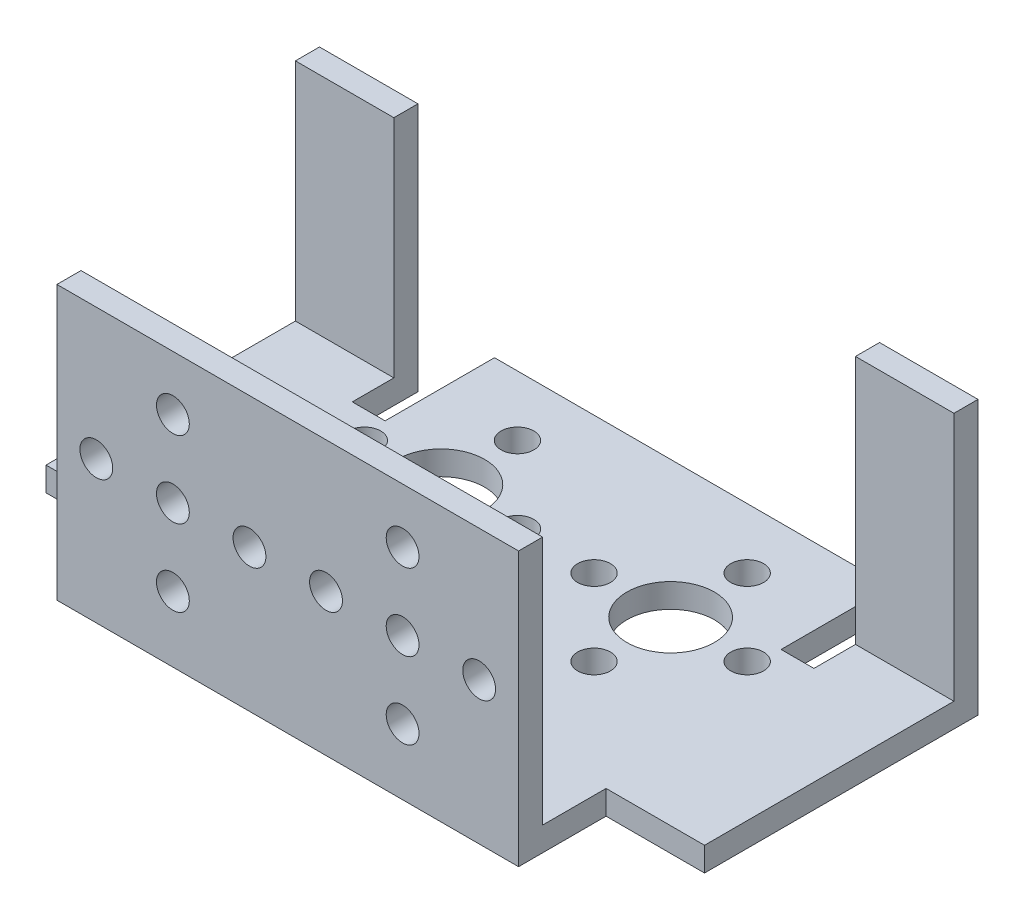
SolidWorks part; units mm, degrees
ref_plane "Front Plane" through (0, 0, 0) normal (0, 0, 1) x (1, 0, 0)
ref_plane "Top Plane" through (0, 0, 0) normal (0, 1, 0) x (1, 0, 0)
ref_plane "Right Plane" through (0, 0, 0) normal (1, 0, 0) x (0, 0, -1)
sketch "Sketch1" plane through (0, 0, 0) normal (0, 1, 0) x (1, 0, 0)
  line L0 (0, 0) -> (0, 37) construction
  line L1 (21.1, 0) -> (-21.1, 0)
  line L2 (-21.1, 0) -> (-21.1, 8)
  line L3 (-21.1, 8) -> (-30.1, 8)
  line L4 (-30.1, 8) -> (-30.1, 33)
  line L5 (-30.1, 33) -> (-21.1, 33)
  line L6 (-21.1, 33) -> (-21.1, 27)
  line L7 (-21.1, 27) -> (-18.1, 27)
  line L8 (-18.1, 27) -> (-18.1, 37)
  line L9 (-18.1, 37) -> (18.1, 37)
  line L10 (18.1, 27) -> (18.1, 37)
  line L11 (21.1, 27) -> (18.1, 27)
  line L12 (21.1, 33) -> (21.1, 27)
  line L13 (30.1, 33) -> (21.1, 33)
  line L14 (30.1, 8) -> (30.1, 33)
  line L15 (21.1, 8) -> (30.1, 8)
  line L16 (21.1, 0) -> (21.1, 8)
  dimension "D1" = 9
  dimension "D2" = 21.1
  dimension "D3" = 37
  dimension "D4" = 8
  dimension "D5" = 25
  dimension "D6" = 6
  dimension "D7" = 3
extrude "Boss-Extrude1" add sketch "Sketch1" along normal blind 2.2
sketch "Sketch2" plane through (0, 2.2, 0) normal (0, 1, 0) x (1, 0, 0)
  line L1 (30.1, 33) -> (21.1, 33)
  line L2 (30.1, 33) -> (30.1, 30.8)
  line L3 (30.1, 30.8) -> (21.1, 30.8)
  line L4 (21.1, 33) -> (21.1, 30.8)
  line L5 (-30.1, 33) -> (-30.1, 8) construction
  line L6 (-21.1, 33) -> (-30.1, 33)
  line L7 (-21.1, 33) -> (-21.1, 30.8)
  line L8 (-21.1, 30.8) -> (-30.1, 30.8)
  line L9 (-30.1, 33) -> (-30.1, 30.8)
  line L11 (21.1, 0) -> (-21.1, 0)
  line L12 (21.1, 0) -> (21.1, 2.2)
  line L13 (21.1, 2.2) -> (-21.1, 2.2)
  line L14 (-21.1, 0) -> (-21.1, 2.2)
  line L15 (21.1, 33) -> (21.1, 27) construction
  line L16 (-21.1, 8) -> (-21.1, 0) construction
  dimension "D1" = 2.2
  dimension "D2" = 2.2
extrude "Boss-Extrude2" add sketch "Sketch2" along normal blind 22.8
sketch "Sketch3" plane through (0, 0, -30.8) normal (0, 0, 1) x (1, 0, 0)
  line L0 (-21.1, 25) -> (-21.1, 2.2) construction
  line L1 (-30.1, 25) -> (-21.1, 25)
  line L2 (-30.1, 25) -> (-30.1, 22.8)
  line L3 (-30.1, 22.8) -> (-21.1, 22.8)
  line L4 (-21.1, 25) -> (-21.1, 22.8)
  dimension "D1" = 2.2
extrude "Cut-Extrude1" cut sketch "Sketch3" against normal through all
sketch "Sketch4" plane through (0, 0, 0) normal (0, 0, 1) x (1, 0, 0)
  line L0 (-21.1, 13) -> (21.1, 13) construction
  line L1 (-21.1, 25) -> (-21.1, 0) construction
  line L2 (21.1, 25) -> (21.1, 0) construction
  line L3 (-21.1, 25) -> (21.1, 25) construction
  line L4 (0, 0) -> (0, 25) construction
  circle A0 centre (-17.5, 13) radius 1.5
  circle A1 centre (-10.5, 13) radius 1.5
  circle A2 centre (-10.5, 20) radius 1.5
  circle A3 centre (-3.5, 13) radius 1.5
  circle A4 centre (-10.5, 6) radius 1.5
  circle A5 centre (10.5, 6) radius 1.5
  circle A6 centre (3.5, 13) radius 1.5
  circle A7 centre (10.5, 20) radius 1.5
  circle A8 centre (10.5, 13) radius 1.5
  circle A9 centre (17.5, 13) radius 1.5
  point P26 (-10.5, 13)
  point P33 (10.5, 13)
  dimension "D1" = 12
  dimension "D2" = 10.5
  dimension "D3" = 3
  dimension "D4" = 7
  dimension "D5" = 4
extrude "Cut-Extrude2" cut sketch "Sketch4" against normal through all
sketch "Sketch5" plane through (0, 2.2, 0) normal (0, 1, 0) x (1, 0, 0)
  line L0 (18.1, 37) -> (-18.1, 37) construction
  line L1 (0, 0) -> (0, 37) construction
  line L2 (-30.1, 24.5) -> (30.1, 24.5) construction
  line L3 (-30.1, 30.8) -> (-30.1, 8) construction
  line L4 (30.1, 8) -> (30.1, 30.8) construction
  circle A0 centre (-10.5, 24.5) radius 4
  circle A1 centre (-17.5, 24.5) radius 1.5
  circle A2 centre (-10.5, 31.5) radius 1.5
  circle A3 centre (-3.5, 24.5) radius 1.5
  circle A4 centre (-10.5, 17.5) radius 1.5
  circle A5 centre (10.5, 17.5) radius 1.5
  circle A6 centre (3.5, 24.5) radius 1.5
  circle A7 centre (10.5, 31.5) radius 1.5
  circle A8 centre (17.5, 24.5) radius 1.5
  circle A9 centre (10.5, 24.5) radius 4
  point P24 (-10.5, 24.5)
  point P34 (10.5, 24.5)
  dimension "D2" = 8
  dimension "D3" = 10.5
  dimension "D4" = 7
  dimension "D5" = 3
  dimension "D1" = 12.5
  dimension "D6" = 4
extrude "Cut-Extrude3" cut sketch "Sketch5" against normal through all
